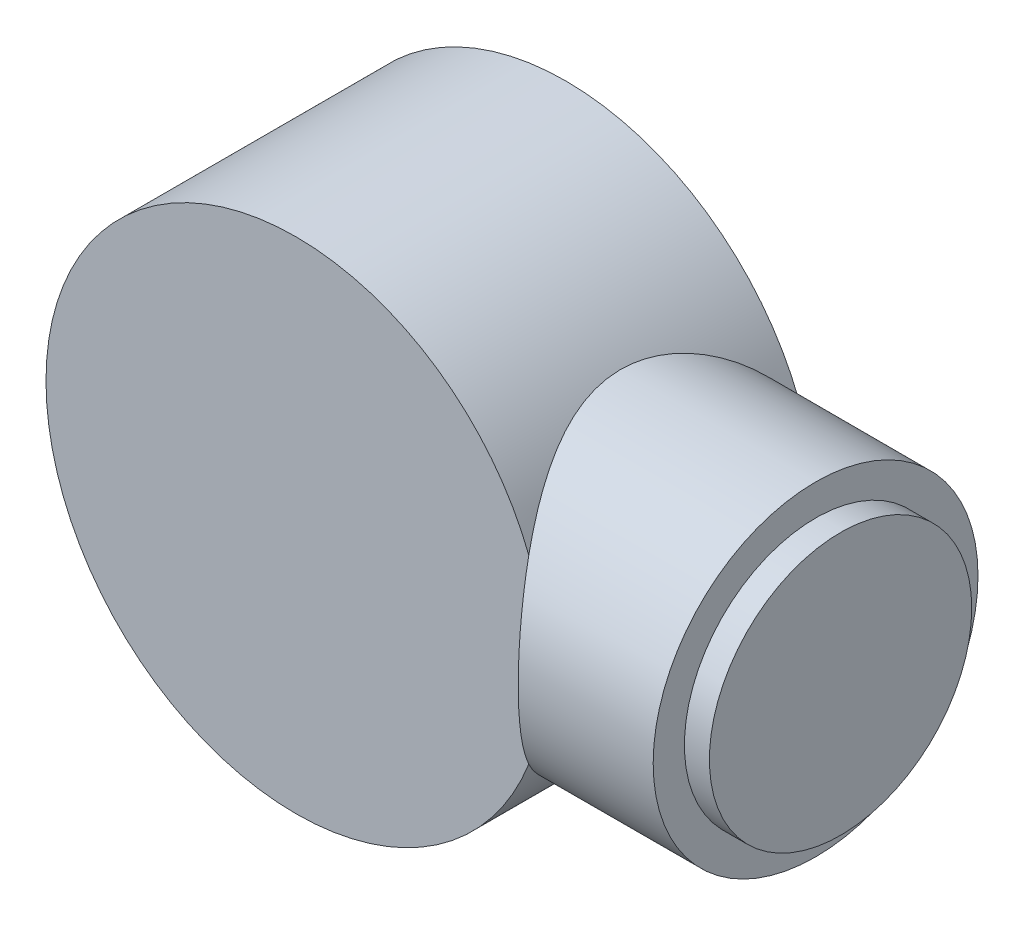
SolidWorks part; units mm, degrees
ref_plane "Front Plane" through (0, 0, 0) normal (0, 0, 1) x (1, 0, 0)
ref_plane "Top Plane" through (0, 0, 0) normal (0, 1, 0) x (1, 0, 0)
ref_plane "Right Plane" through (0, 0, 0) normal (1, 0, 0) x (0, 0, -1)
sketch "Sketch1" plane through (0, 0, 0) normal (0, 0, 1) x (1, 0, 0)
  circle A0 centre (0, 0) radius 50
  dimension "D1" = 100
extrude "Boss-Extrude1" add sketch "Sketch1" along normal blind 54
ref_plane "Plane1" through (77, 0, 0) normal (1, 0, 0) x (0, 0, -1)
sketch "Sketch2" plane through (77, 0, 0) normal (1, 0, 0) x (0, 0, -1)
  circle A0 centre (-27, 0) radius 32.5
  dimension "D1" = 65
  dimension "D2" = 27
extrude "Boss-Extrude2" add sketch "Sketch2" against normal up to surface (27 mm away) up to face at (50, 0, 54)
sketch "Sketch3" plane through (77, 0, 0) normal (1, 0, 0) x (0, 0, -1)
  circle A0 centre (-27, 0) radius 26.25
  dimension "D1" = 52.5
extrude "Boss-Extrude3" add sketch "Sketch3" along normal blind 5
